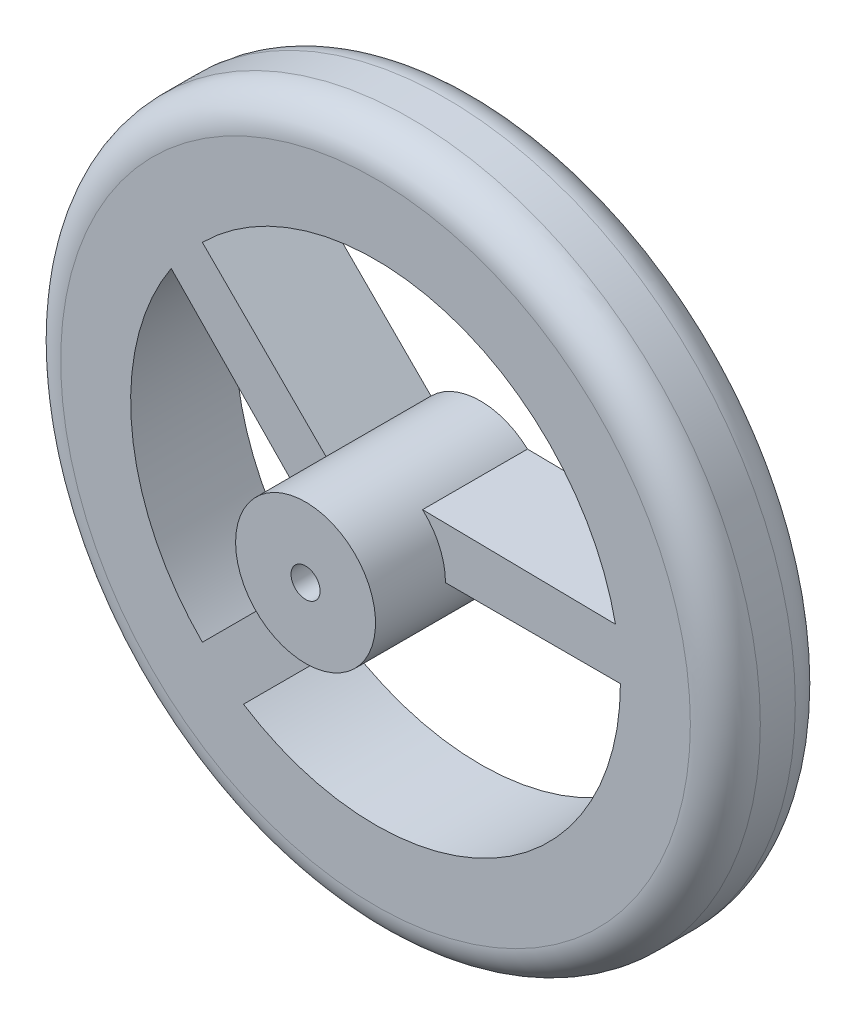
SolidWorks part; units mm, degrees
material "Rubber"
ref_plane "Front Plane" through (0, 0, 0) normal (0, 0, 1) x (1, 0, 0)
ref_plane "Top Plane" through (0, 0, 0) normal (0, 1, 0) x (1, 0, 0)
ref_plane "Right Plane" through (0, 0, 0) normal (1, 0, 0) x (0, 0, -1)
sketch "Sketch1" plane through (0, 0, 0) normal (0, 0, 1) x (1, 0, 0)
  line L1 (-10.6066, -10.6066) -> (-49.4975, -49.4975)
  line L4 (10.6066, -10.6066) -> (-37.7411, -58.9543)
  line L5 (-10.6066, -10.6066) -> (-49.4967, -49.4967)
  line L6 (-49.2269, -49.7666) -> (-49.4967, -49.4967)
  line L8 (-10.6066, 10.6066) -> (-49.4975, 49.4975)
  line L9 (-10.6066, -10.6066) -> (-58.3969, 38.5979)
  line L12 (15, 0) -> (70, 0)
  line L13 (0, 15) -> (68.5857, 14)
  arc A0 (-58.3969, 38.5979) -> (-49.2269, -49.7666) centre (0, 0) ccw
  circle A1 centre (0, 0) radius 100
  circle A2 centre (0, 0) radius 15
  arc A3 (-37.7411, -58.9543) -> (70, 0) centre (0, 0) ccw
  arc A4 (68.5857, 14) -> (-49.4975, 49.4975) centre (0, 0) ccw
  point P4 (-10.6066, -10.6066)
  point P8 (10.6066, -10.6066)
  point P9 (0, 15)
  dimension "D1" = 200
  dimension "D2" = 140
  dimension "D4" = 15
  dimension "D5" = 15
  dimension "D6" = 15
extrude "Boss-Extrude1" add sketch "Sketch1" along normal blind 30 contours A1 A4 L13 A2 L12 A3 L4 L1 L6 A0 L9 L8 | A2 L9 L13
fillet "Fillet2" radius 10 2 edges at (100, 0, 30) (100, 0, 0)
sketch "Sketch2" plane through (0, 0, 0) normal (0, 0, -1) x (-1, 0, 0)
  circle A0 centre (0, 0) radius 20
  circle A1 centre (0, 0) radius 4.15
  dimension "D1" = 40
  dimension "D2" = 8.3
extrude "Boss-Extrude2" add sketch "Sketch2" against normal blind 50
scale "Scale1" scale about centroid uniform scaling yes scale factor 0.05
scale "Scale2" scale about centroid uniform scaling yes scale factor 6
